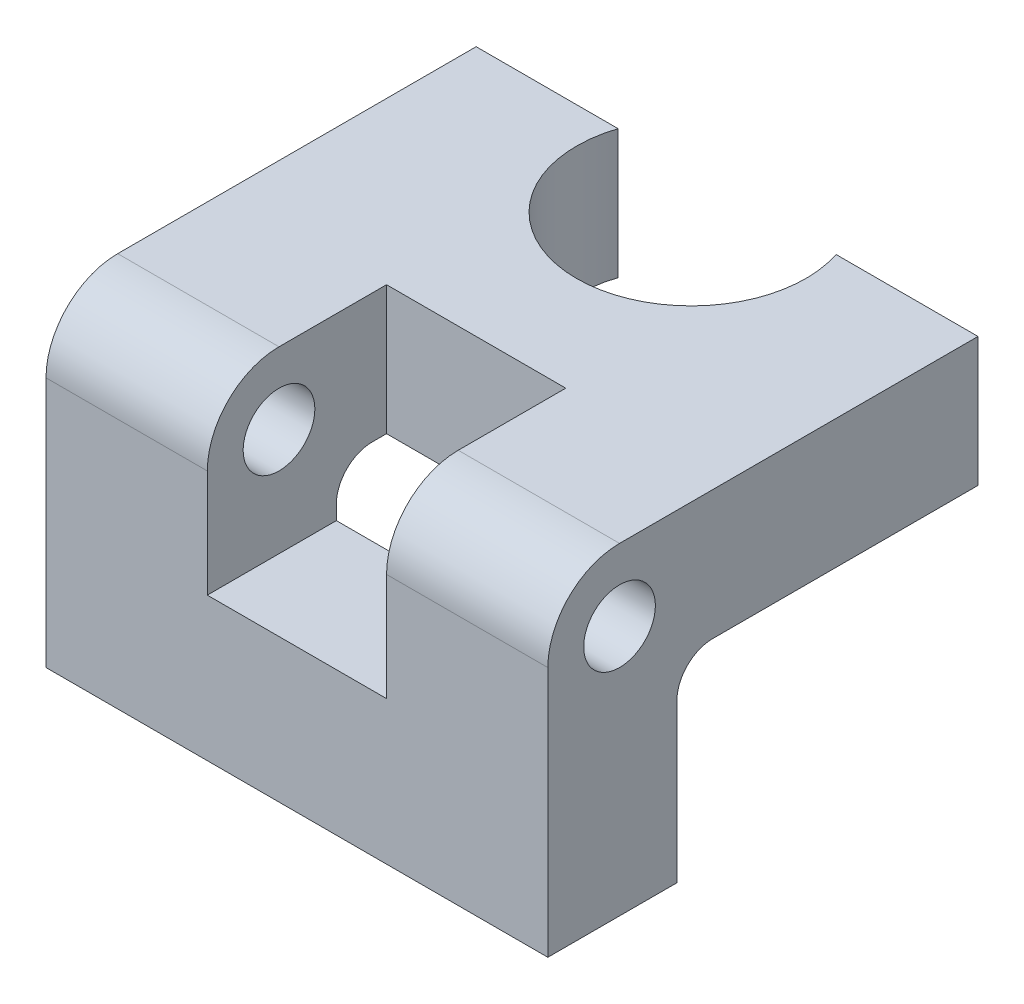
SolidWorks part; units mm, degrees
ref_plane "정면" through (0, 0, 0) normal (0, 0, 1) x (1, 0, 0)
ref_plane "윗면" through (0, 0, 0) normal (0, 1, 0) x (1, 0, 0)
ref_plane "우측면" through (0, 0, 0) normal (1, 0, 0) x (0, 0, -1)
sketch "Sketch1" plane through (0, 0, 0) normal (0, 1, 0) x (1, 0, 0)
  line L1 (0, 0) -> (70, 0)
  line L2 (0, 0) -> (0, 60)
  line L3 (0, 60) -> (70, 60)
  line L4 (70, 0) -> (70, 60)
  dimension "D1" = 70
  dimension "D2" = 60
extrude "Boss-Extrude1" add sketch "Sketch1" along normal blind 45
sketch "Sketch2" plane through (70, 0, 0) normal (1, 0, 0) x (0, 0, -1)
  line L0 (18, 0) -> (18, 27)
  line L1 (0, 0) -> (60, 0) construction
  line L2 (18, 27) -> (60, 27)
  line L3 (60, 45) -> (60, 0) construction
  line L4 (60, 27) -> (60, 0)
  line L5 (60, 0) -> (18, 0)
  line L6 (0, 45) -> (60, 45) construction
  line L7 (0, 45) -> (0, 0) construction
  dimension "D1" = 18
  dimension "D2" = 18
extrude "Cut-Extrude1" cut sketch "Sketch2" against normal through all
sketch "Sketch3" plane through (0, 45, 0) normal (0, 1, 0) x (1, 0, 0)
  line L0 (70, 60) -> (0, 60) construction
  line L1 (0, 60) -> (0, 0) construction
  circle A0 centre (35, 55) radius 16
  dimension "D1" = 32
  dimension "D2" = 5
  dimension "D3" = 35
extrude "Cut-Extrude2" cut sketch "Sketch3" against normal blind 45
sketch "Sketch4" plane through (0, 0, 0) normal (0, 0, 1) x (1, 0, 0)
  line L0 (0, 45) -> (70, 45) construction
  line L1 (22.5, 45) -> (47.5, 45)
  line L2 (22.5, 45) -> (22.5, 20)
  line L3 (22.5, 20) -> (47.5, 20)
  line L4 (47.5, 45) -> (47.5, 20)
  line L5 (70, 45) -> (70, 0) construction
  dimension "D1" = 25
  dimension "D2" = 25
  dimension "D3" = 22.5
extrude "Cut-Extrude3" cut sketch "Sketch4" against normal blind 25
fillet "Fillet1" radius 10 2 edges at (58.75, 45, 0) (11.25, 45, 0)
fillet "Fillet2" radius 5 2 edges at (11.25, 27, -18) (58.75, 27, -18)
sketch "Sketch9" plane through (70, 0, 0) normal (1, 0, 0) x (0, 0, -1)
  circle A0 centre (10, 35) radius 5
  dimension "D1" = 10
extrude "Cut-Extrude4" cut sketch "Sketch9" against normal through all contours A0
